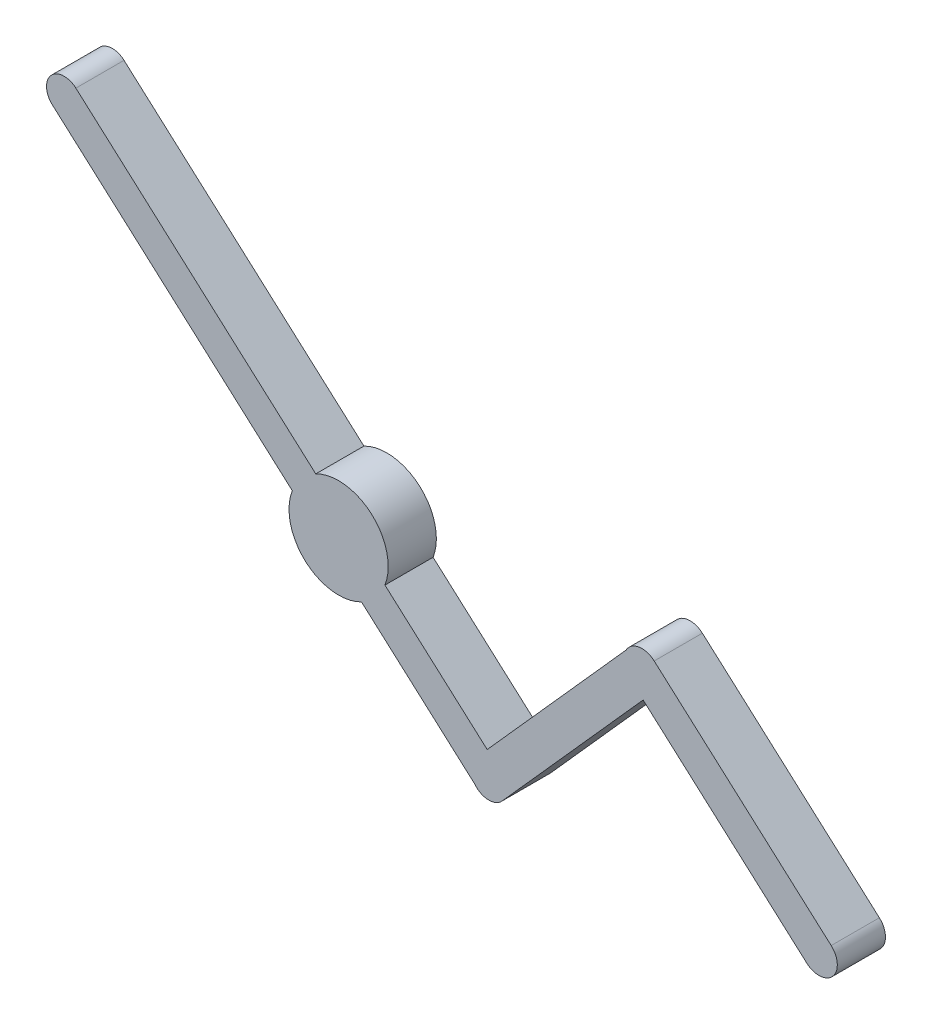
SolidWorks part; units mm, degrees
material "7075-T6 (SN)"
ref_plane "前视基准面" through (0, 0, 0) normal (0, 0, 1) x (1, 0, 0)
ref_plane "上视基准面" through (0, 0, 0) normal (0, 1, 0) x (1, 0, 0)
ref_plane "右视基准面" through (0, 0, 0) normal (1, 0, 0) x (0, 0, -1)
sketch "草图1" plane through (0, 0, 0) normal (0, 0, 1) x (1, 0, 0)
  line L0 (170.8211, -71.264) -> (170.8211, -68.764)
  line L1 (170.8211, -70.014) -> (178.8831, -53.1508)
  line L2 (178.8831, -53.1508) -> (190.281, -63.3232)
  line L3 (190.281, -63.3232) -> (196.5191, -68.8906)
  line L4 (196.5191, -68.8906) -> (202.878, -61.7657)
  line L5 (202.878, -61.7657) -> (210.2274, -68.3249)
  line L6 (178.8831, -53.1508) -> (196.5191, -68.8906) construction
  line L7 (179.3702, -52.6051) -> (197.0061, -68.3449)
  line L8 (178.3961, -53.6965) -> (196.0321, -69.4363)
  line L9 (196.5191, -68.8906) -> (202.878, -61.7657) construction
  line L10 (195.9639, -68.3951) -> (202.3228, -61.2702)
  line L11 (197.0743, -69.3861) -> (203.4332, -62.2612)
  line L12 (202.878, -61.7657) -> (210.2274, -68.3249) construction
  line L13 (203.3854, -61.1971) -> (210.7348, -67.7563)
  line L14 (202.3706, -62.3342) -> (209.7199, -68.8934)
  arc A0 (179.3702, -52.6051) -> (178.3961, -53.6965) centre (178.8831, -53.1508) ccw
  arc A1 (196.0321, -69.4363) -> (197.0061, -68.3449) centre (196.5191, -68.8906) ccw
  arc A2 (195.9639, -68.3951) -> (197.0743, -69.3861) centre (196.5191, -68.8906) ccw
  arc A3 (203.4332, -62.2612) -> (202.3228, -61.2702) centre (202.878, -61.7657) ccw
  arc A4 (203.3854, -61.1971) -> (202.3706, -62.3342) centre (202.878, -61.7657) ccw
  arc A5 (209.7199, -68.8934) -> (210.7348, -67.7563) centre (210.2274, -68.3249) ccw
  circle A6 centre (190.281, -63.3232) radius 2.0592
  point P8 (187.7011, -61.0207)
  point P13 (199.6985, -65.3281)
  point P19 (206.5527, -65.0453)
extrude "凸台-拉伸1" add sketch "草图1" along normal blind 2
